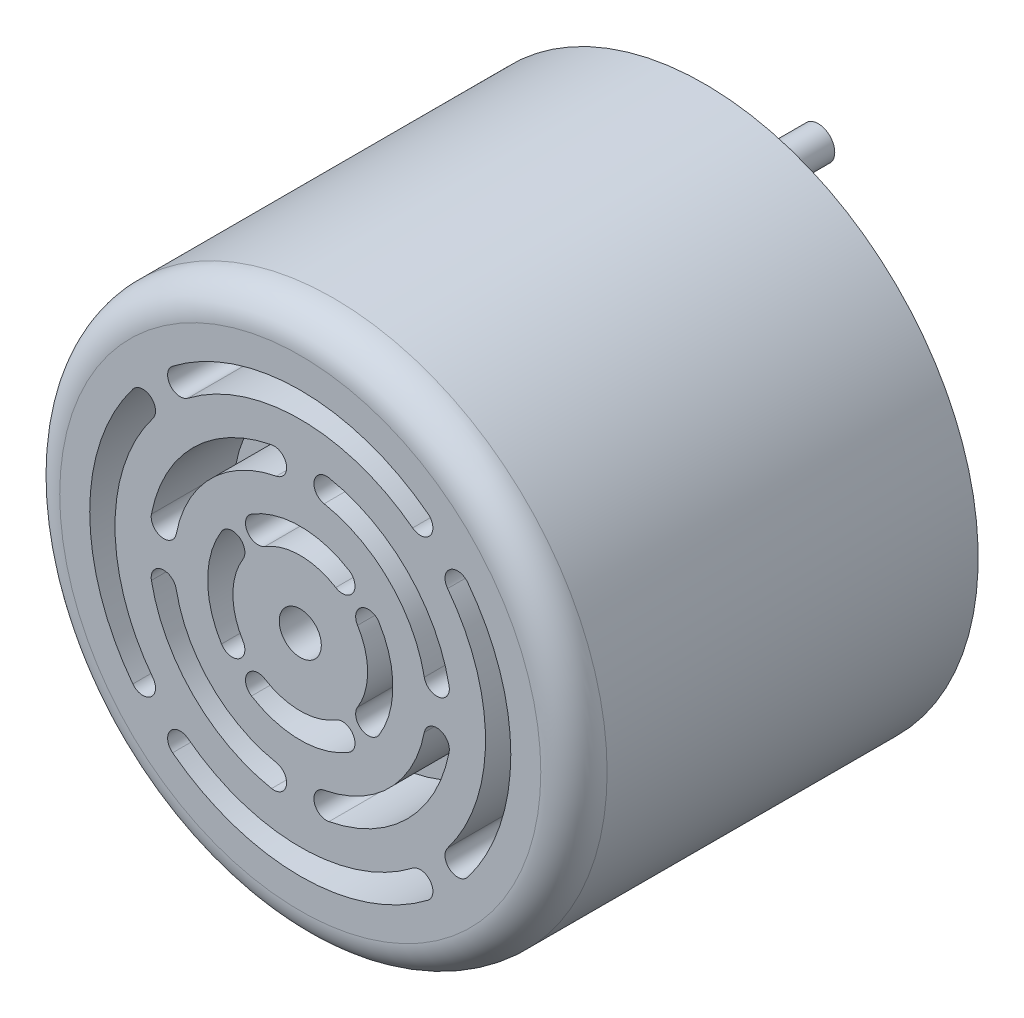
SolidWorks part; units mm, degrees
ref_plane "Front" through (0, 0, 0) normal (0, 0, 1) x (1, 0, 0)
ref_plane "Top" through (0, 0, 0) normal (0, 1, 0) x (1, 0, 0)
ref_plane "Right" through (0, 0, 0) normal (1, 0, 0) x (0, 0, -1)
sketch "Sketch1" plane through (0, 0, 0) normal (0, 0, 1) x (1, 0, 0)
  circle A0 centre (0, 0) radius 8.255
  dimension "D1" = 16.51
extrude "Extrude1" add sketch "Sketch1" along normal mid plane 12.192
sketch "Sketch2" plane through (0, 0, -6.096) normal (0, 0, -1) x (-1, 0, 0)
  circle A1 centre (0, 5) radius 0.5
  dimension "D1" = 1
  dimension "D2" = 5
extrude "Extrude2" add sketch "Sketch2" along normal blind 3.429
mirror "Mirror1" about plane through (0, 0, 0) normal (0, 1, 0) of "Extrude2"
fillet "Fillet1" radius 1 1 edges at (8.255, 0, 6.096)
sketch "Sketch3" plane through (0, 0, 6.096) normal (0, 0, 1) x (1, 0, 0)
  line L0 (0, -5.969) -> (0, 5.969) construction
  line L1 (0, 0) -> (4.2207, 4.2207) construction
  circle A0 centre (0, 0) radius 0.635
  arc A1 (3.3885, 4.4434) -> (3.8505, 5.0493) centre (3.6195, 4.7464) ccw
  arc A2 (3.8505, 5.0493) -> (-3.8505, 5.0493) centre (0, 0) ccw
  arc A3 (-3.8505, 5.0493) -> (-3.3885, 4.4434) centre (-3.6195, 4.7464) ccw
  arc A4 (3.3885, 4.4434) -> (-3.3885, 4.4434) centre (0, 0) ccw
  arc A5 (3.7412, 0.7206) -> (4.4895, 0.8647) centre (4.1154, 0.7927) ccw
  arc A6 (4.4895, 0.8647) -> (0.8647, 4.4895) centre (0, 0) ccw
  arc A7 (0.8647, 4.4895) -> (0.7206, 3.7412) centre (0.7927, 4.1154) ccw
  arc A8 (3.7412, 0.7206) -> (0.7206, 3.7412) centre (0, 0) ccw
  arc A9 (1.0695, 1.7278) -> (1.4705, 2.3757) centre (1.27, 2.0517) ccw
  arc A10 (1.4705, 2.3757) -> (-1.4705, 2.3757) centre (0, 0) ccw
  arc A11 (-1.4705, 2.3757) -> (-1.0695, 1.7278) centre (-1.27, 2.0517) ccw
  arc A12 (1.0695, 1.7278) -> (-1.0695, 1.7278) centre (0, 0) ccw
  circle A13 centre (0, 0) radius 4.191 construction
  circle A14 centre (0, 0) radius 2.413 construction
  circle A15 centre (0, 0) radius 5.969 construction
  dimension "D1" = 1.27
  dimension "D2" = 4.826
  dimension "D3" = 8.382
  dimension "D4" = 11.938
  dimension "D5" = 0.381
  dimension "D8" = 4.699
  dimension "D6" = 2.54
  dimension "D7" = 7.239
  dimension "D9" = 45
extrude "Cut-Extrude1" cut sketch "Sketch3" against normal blind 2.54
pattern_circular "CirPattern1" count 4 over 360 about axis through (0, 0, 0) along (0, 0, 1) of "Cut-Extrude1"
